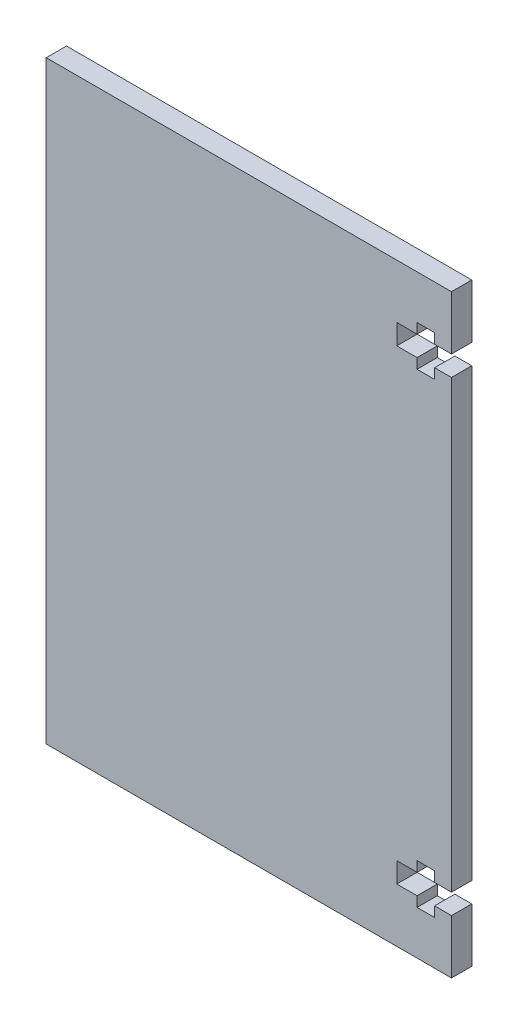
SolidWorks part; units mm, degrees
ref_plane "前视基准面" through (0, 0, 0) normal (0, 0, 1) x (1, 0, 0)
ref_plane "上视基准面" through (0, 0, 0) normal (0, 1, 0) x (1, 0, 0)
ref_plane "右视基准面" through (0, 0, 0) normal (1, 0, 0) x (0, 0, -1)
sketch "草图1" plane through (0, 0, 0) normal (0, 0, 1) x (1, 0, 0)
  line L0 (0, 44) -> (0, 36)
  line L1 (-2.5, 36) -> (-2.5, 37.5)
  line L2 (-2.5, 33) -> (-2.5, 31.5)
  line L3 (0, 33) -> (-2.5, 33)
  line L4 (-2.5, 37.5) -> (-5.1, 37.5)
  line L5 (-5.1, 37.5) -> (-5.1, 36)
  line L6 (-5.1, 36) -> (-8.1, 36)
  line L7 (-8.1, 33) -> (-8.1, 36)
  line L8 (-5.1, 33) -> (-8.1, 33)
  line L9 (-5.1, 31.5) -> (-5.1, 33)
  line L10 (-2.5, 31.5) -> (-5.1, 31.5)
  line L11 (-2.5, 36) -> (0, 36)
  line L12 (0, -44) -> (0, -36)
  line L13 (0, -33) -> (0, 33)
  line L14 (-2.5, -33) -> (-2.5, -31.5)
  line L15 (-2.5, -36) -> (-2.5, -37.5)
  line L16 (0, -36) -> (-2.5, -36)
  line L17 (-2.5, -31.5) -> (-5.1, -31.5)
  line L18 (-5.1, -31.5) -> (-5.1, -33)
  line L19 (-5.1, -33) -> (-8.1, -33)
  line L20 (-8.1, -36) -> (-8.1, -33)
  line L21 (-5.1, -36) -> (-8.1, -36)
  line L22 (-5.1, -37.5) -> (-5.1, -36)
  line L23 (-2.5, -37.5) -> (-5.1, -37.5)
  line L24 (-2.5, -33) -> (0, -33)
  line L25 (0, 44) -> (-60, 44)
  line L26 (-60, 44) -> (-60, -44)
  line L27 (-60, -44) -> (0, -44)
  dimension "D1" = 88
  dimension "D2" = 60
extrude "凸台-拉伸1" add sketch "草图1" along normal blind 3
sketch "草图2" plane through (0, 0, 0) normal (1, 0, 0) x (0, 0, -1)
  line L0 (-1.5, 36) -> (-1.5, 33)
  line L1 (-3, 36) -> (0, 36) construction
  line L2 (-3, 33) -> (0, 33) construction
  circle A0 centre (-1.5, 34.5) radius 1.5
